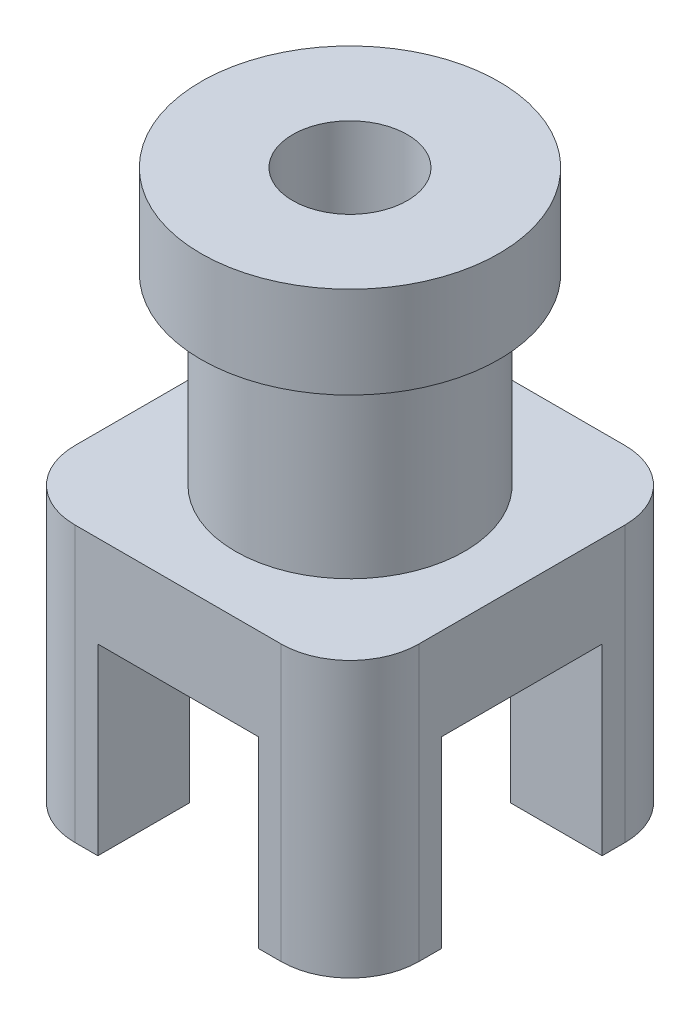
SolidWorks part; units mm, degrees
ref_plane "Alzado" through (0, 0, 0) normal (0, 0, 1) x (1, 0, 0)
ref_plane "Planta" through (0, 0, 0) normal (0, 1, 0) x (1, 0, 0)
ref_plane "Vista lateral" through (0, 0, 0) normal (1, 0, 0) x (0, 0, -1)
sketch "Croquis2" plane through (0, 0, 0) normal (0, 1, 0) x (1, 0, 0)
  line L1 (75, 75) -> (-75, 75)
  line L2 (75, 75) -> (75, -75)
  line L3 (75, -75) -> (-75, -75)
  line L4 (-75, 75) -> (-75, -75)
  line L5 (75, 75) -> (-75, -75) construction
  line L6 (75, -75) -> (-75, 75) construction
  point P0 (0, 0)
  dimension "D1" = 150
  dimension "D2" = 150
extrude "Saliente-Extruir2" add sketch "Croquis2" along normal blind 40
sketch "Croquis3" plane through (0, 0, 0) normal (0, -1, 0) x (1, 0, 0)
  line L1 (-75, 75) -> (-35, 75)
  line L2 (-75, 75) -> (-75, 35)
  line L3 (-75, 35) -> (-35, 35)
  line L4 (-35, 75) -> (-35, 35)
  line L5 (75, 75) -> (35, 75)
  line L6 (75, 75) -> (75, 35)
  line L7 (75, 35) -> (35, 35)
  line L8 (35, 75) -> (35, 35)
  line L9 (-75, -75) -> (-35, -75)
  line L10 (-75, -75) -> (-75, -35)
  line L11 (-75, -35) -> (-35, -35)
  line L12 (-35, -75) -> (-35, -35)
  line L13 (75, -75) -> (35, -75)
  line L14 (75, -75) -> (75, -35)
  line L15 (75, -35) -> (35, -35)
  line L16 (35, -75) -> (35, -35)
  dimension "D1" = 40
  dimension "D2" = 40
  dimension "D3" = 40
  dimension "D4" = 40
extrude "Saliente-Extruir3" add sketch "Croquis3" along normal blind 80
sketch "Croquis4" plane through (0, 40, 0) normal (0, 1, 0) x (1, 0, 0)
  circle A0 centre (0, 0) radius 50
  dimension "D1" = 100
extrude "Saliente-Extruir4" add sketch "Croquis4" along normal blind 120
sketch "Croquis5" plane through (0, 160, 0) normal (0, 1, 0) x (1, 0, 0)
  circle A0 centre (0, 0) radius 25
  dimension "D1" = 50
extrude "Cortar-Extruir1" cut sketch "Croquis5" against normal blind 221
fillet "Redondeo1" radius 30 4 edges at (-75, -20, -75) (75, -20, -75) (75, -20, 75) (-75, -20, 75)
sketch "Croquis6" plane through (0, 160, 0) normal (0, 1, 0) x (1, 0, 0)
  circle A0 centre (0, 0) radius 65
  dimension "D1" = 130
extrude "Saliente-Extruir5" add sketch "Croquis6" against normal blind 40
sketch "Croquis7" plane through (0, 160, 0) normal (0, 1, 0) x (1, 0, 0)
  circle A0 centre (0, 0) radius 25
  dimension "D1" = 50
extrude "Cortar-Extruir2" cut sketch "Croquis7" against normal blind 125
